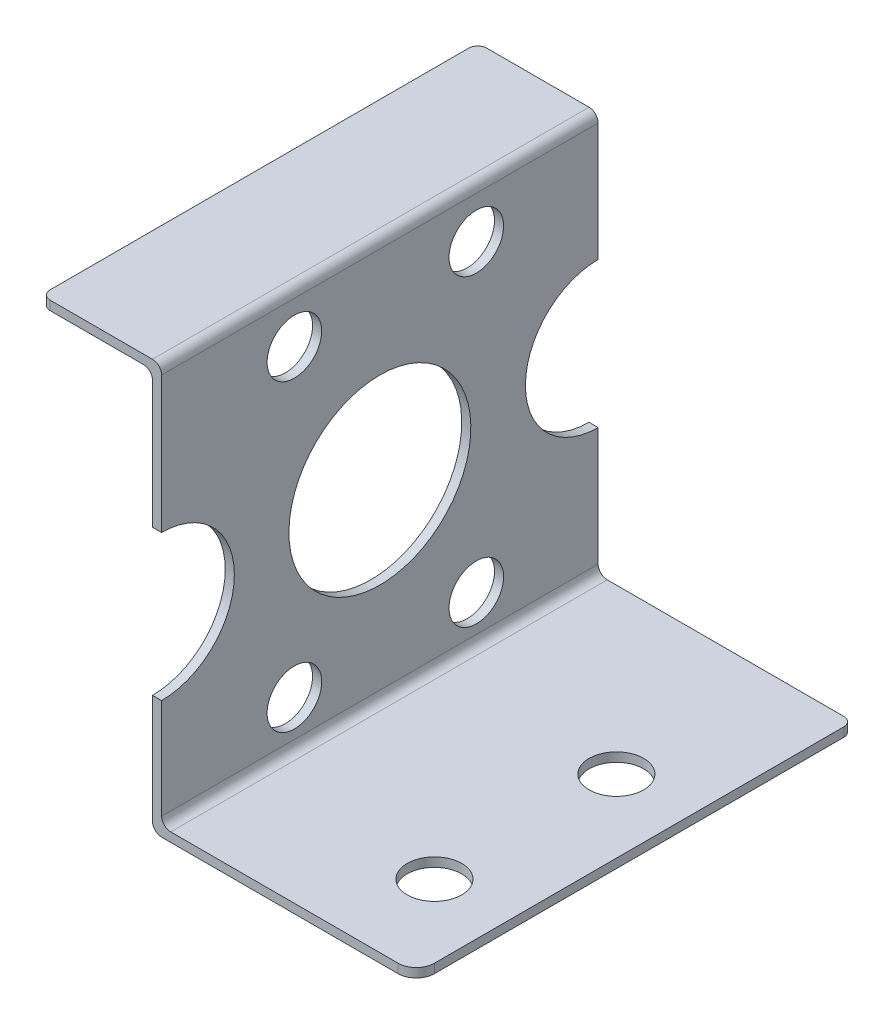
SolidWorks part; units mm, degrees
ref_plane "Front Plane" through (0, 0, 0) normal (0, 0, 1) x (1, 0, 0)
ref_plane "Top Plane" through (0, 0, 0) normal (0, 1, 0) x (1, 0, 0)
ref_plane "Right Plane" through (0, 0, 0) normal (1, 0, 0) x (0, 0, -1)
sketch "Sketch1" plane through (0, 0, 0) normal (0, 0, 1) x (1, 0, 0)
  line L0 (0, 22) -> (0, 0)
  line L1 (0, 0) -> (14, 0)
  line L2 (0, 22) -> (-6.621, 22)
  dimension "D1" = 22
  dimension "D2" = 14
extrude "Extrude-Thin1" add sketch "Sketch1" along normal blind 24 thin
sketch "Sketch2" plane through (0, 0, 0) normal (0, 1, 0) x (1, 0, 0)
  line L0 (0, -24) -> (14, -24) construction
  line L1 (14, -24) -> (14, 0) construction
  circle A0 centre (10, -19) radius 1.5
  circle A1 centre (10, -9) radius 1.5
  dimension "D1" = 3
  dimension "D2" = 5
  dimension "D3" = 4
  dimension "D4" = 2
extrude "Cut-Extrude1" cut sketch "Sketch2" against normal blind 10
sketch "Sketch3" plane through (0, 0, 0) normal (1, 0, 0) x (0, 0, -1)
  line L0 (-24, 22) -> (-24, 0) construction
  line L2 (-24, 22) -> (0, 22) construction
  circle A0 centre (-16.7, 19.2) radius 1.5
  circle A4 centre (-16.7, 2.5) radius 1.5
  circle A5 centre (-6.7, 19.2) radius 1.5
  circle A6 centre (-6.7, 2.5) radius 1.5
  dimension "D1" = 3
  dimension "D2" = 7.3
  dimension "D3" = 16.7
  dimension "D4" = 2.8
  dimension "D5" = 2
  dimension "D6" = 2
extrude "Cut-Extrude2" cut sketch "Sketch3" against normal blind 10
fillet "Fillet1" radius 1 1 edges at (14, -0.25, 24)
fillet "Fillet2" radius 0.5 6 edges at (-0.5, -0.5, 12) (-0.5, 21.5, 12) (-6.621, 21.75, 24) (-6.621, 21.75, 0) (0, 0, 12) (14, -0.25, 0)
fillet "Fillet3" radius 0.5 1 edges at (0, 22, 12)
sketch "Sketch4" plane through (0, 0, 0) normal (1, 0, 0) x (0, 0, -1)
  line L0 (0, 21.5) -> (0, 0.5) construction
  line L4 (0, 0) -> (-24, 0) construction
  circle A0 centre (-12, 10.5) radius 5
  dimension "D3" = 10
  dimension "D1" = 12
  dimension "D2" = 10.5
extrude "Cut-Extrude3" cut sketch "Sketch4" against normal blind 10
sketch "Sketch5" plane through (0, 0, 0) normal (1, 0, 0) x (0, 0, -1)
  line L0 (0, 21.5) -> (0, 0.5) construction
  line L1 (0, 21.5) -> (-24, 21.5) construction
  line L2 (0, 15) -> (0, 7)
  line L3 (-24, 21.5) -> (-24, 0.5) construction
  line L4 (-24, 14) -> (-24, 6)
  arc A0 (0, 15) -> (0, 7) centre (0, 11) ccw
  arc A1 (-24, 14) -> (-24, 6) centre (-24, 10) cw
  dimension "D1" = 4
  dimension "D3" = 4
  dimension "D2" = 10.5
extrude "Cut-Extrude5" cut sketch "Sketch5" against normal blind 10
